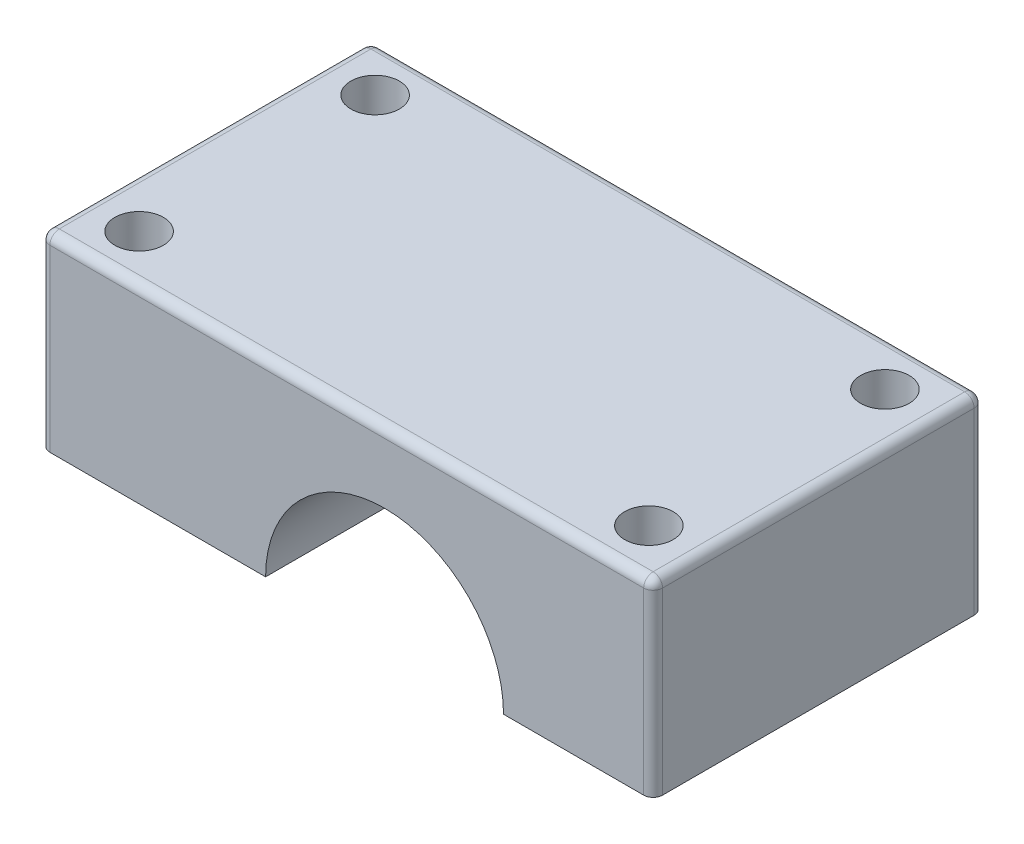
SolidWorks part; units mm, degrees
ref_plane "Front Plane" through (0, 0, 0) normal (0, 0, 1) x (1, 0, 0)
ref_plane "Top Plane" through (0, 0, 0) normal (0, 1, 0) x (1, 0, 0)
ref_plane "Right Plane" through (0, 0, 0) normal (1, 0, 0) x (0, 0, -1)
sketch "Sketch1" plane through (0, 0, 0) normal (0, 1, 0) x (1, 0, 0)
  line L1 (-36.1315, 22.225) -> (36.1315, 22.225)
  line L2 (-36.1315, 22.225) -> (-36.1315, -22.225)
  line L3 (-36.1315, -22.225) -> (36.1315, -22.225)
  line L4 (36.1315, 22.225) -> (36.1315, -22.225)
  line L5 (-36.1315, 22.225) -> (36.1315, -22.225) construction
  line L6 (-36.1315, -22.225) -> (36.1315, 22.225) construction
  point P0 (0, 0)
  dimension "D1" = 72.263
  dimension "D2" = 44.45
extrude "Boss-Extrude1" add sketch "Sketch1" along normal mid plane 25.4
sketch "Sketch2" plane through (0, 0, 22.225) normal (0, 0, 1) x (1, 0, 0)
  line L0 (-36.1315, -12.7) -> (36.1315, -12.7) construction
  line L1 (-16.002, -12.7) -> (16.002, -12.7)
  arc A0 (-16.002, -12.7) -> (16.002, -12.7) centre (0, -12.7) cw
  dimension "D1" = 16.002
extrude "Cut-Extrude1" cut sketch "Sketch2" against normal through all
sketch "Sketch3" plane through (-36.1315, 0, 0) normal (-1, 0, 0) x (0, 0, 1)
  line L4 (-22.225, -12.7) -> (22.225, -12.7)
  line L5 (22.225, -12.7) -> (22.225, 12.7)
  line L6 (22.225, 12.7) -> (-22.225, 12.7)
  line L7 (-22.225, 12.7) -> (-22.225, -12.7)
  line L8 (-22.225, -12.7) -> (22.225, -12.7)
  line L9 (22.225, -12.7) -> (22.225, 12.7)
  line L10 (22.225, 12.7) -> (-22.225, 12.7)
  line L11 (-22.225, 12.7) -> (-22.225, -12.7)
  dimension "D1" = 0
extrude "Boss-Extrude2" add sketch "Sketch3" along normal blind 10.16
sketch "Sketch6" plane through (0, -12.7, 0) normal (0, -1, 0) x (1, 0, 0)
  line L0 (-46.2915, 22.225) -> (36.1315, 22.225) construction
  line L1 (-5.08, 22.225) -> (-5.08, -22.225) construction
  line L2 (-16.002, -22.225) -> (16.002, -22.225) construction
  line L3 (29.21, -22.225) -> (29.21, 22.225) construction
  line L4 (-39.37, 15.875) -> (29.21, 15.875)
  line L5 (-39.37, 15.875) -> (-39.37, -15.875)
  line L6 (-39.37, -15.875) -> (29.21, -15.875)
  line L7 (29.21, 15.875) -> (29.21, -15.875)
  line L8 (-39.37, 15.875) -> (29.21, -15.875) construction
  line L9 (-39.37, -15.875) -> (29.21, 15.875) construction
  point P8 (-5.08, 0)
  dimension "D1" = 6.35
  dimension "D2" = 68.58
hole_wizard "1/4 Clearance Hole1" positions "3DSketch1" profile "Sketch7" hole size "1/4" standard "ANSI Inch" end condition through all
sketch3d "3DSketch1"
  point P0 (-39.37, -12.7, 15.875)
  point P3 (29.21, -12.7, 15.875)
  point P6 (29.21, -12.7, -15.875)
  point P9 (-39.37, -12.7, -15.875)
sketch "Sketch7" plane through (-39.37, -12.7, 15.875) normal (1, 0, 0) x (0, 0, -1)
  line L0 (0, 0) -> (0, 25.4)
  line L1 (0, 25.4) -> (3.2639, 25.4)
  line L2 (3.2639, 25.4) -> (3.2639, 0)
  line L5 (3.2639, 0) -> (0, 0)
  line L11 (0, -6.35) -> (0, 107.95) construction
  dimension "Thru Hole Dia." = 6.5278
  dimension "Thru Hole Depth" = 25.4
fillet "Fillet8" radius 1.27 8 edges at (36.1315, 0, -22.225) (-46.2915, 0, -22.225) (-46.2915, 0, 22.225) (36.1315, 0, 22.225) (-5.08, 12.7, -22.225) (36.1315, 12.7, 0) (-46.2915, 12.7, 0) (-5.08, 12.7, 22.225)
ref_plane "Plane1" through (-40.64, 0, 0) normal (1, 0, 0) x (0, 0, -1)
equation "\"0.045n\"=0.04'no idea wtf this is"
equation "\"front angle\"= 75deg"
equation "\"flange thickness\"= .35in'Thickness of the flange that mates with the connector"
equation "\"flange gap\"= 0.272in'Gap for clearance with the Middle Celvis connector"
equation "\"mid and rear length\"=1.75in"
equation "\"D2@Sketch1\"=\"mid and rear length\""
